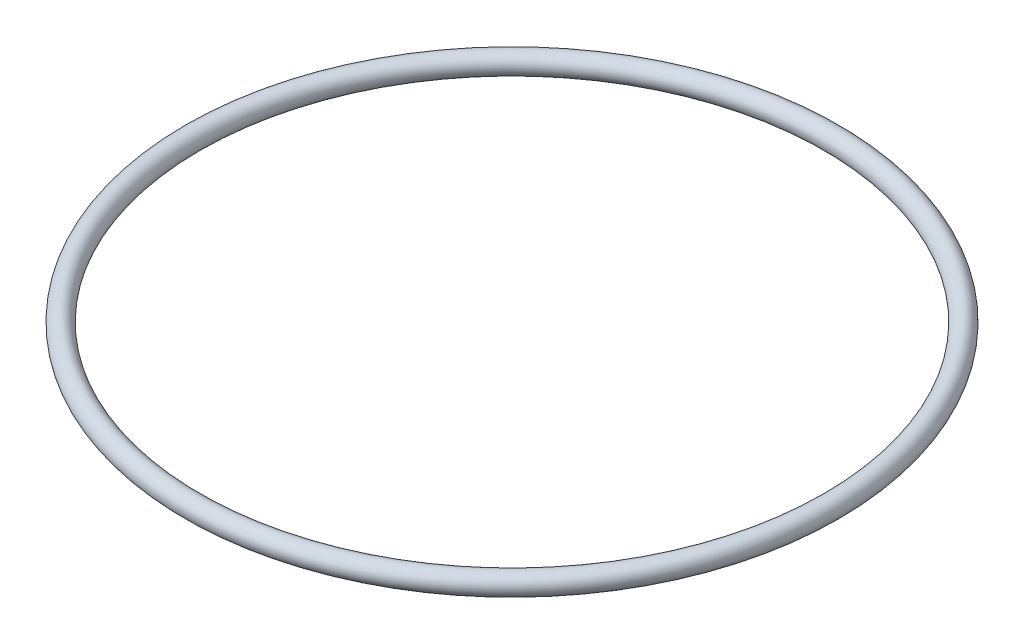
SolidWorks part; units mm, degrees
ref_plane "前视基准面" through (0, 0, 0) normal (0, 0, 1) x (1, 0, 0)
ref_plane "上视基准面" through (0, 0, 0) normal (0, 1, 0) x (1, 0, 0)
ref_plane "右视基准面" through (0, 0, 0) normal (1, 0, 0) x (0, 0, -1)
sketch "草图1" plane through (0, 0, 0) normal (0, 1, 0) x (1, 0, 0)
  circle A0 centre (0, 0) radius 46.25
  dimension "D1" = 92.5
sketch "草图2" plane through (0, 0, 0) normal (0, 0, 1) x (1, 0, 0)
  line L0 (46.25, 0) -> (-46.25, 0) construction
  circle A0 centre (46.25, 0) radius 1.5
  dimension "D1" = 3
sweep "扫描1" add profiles "草图2" path "草图1"
